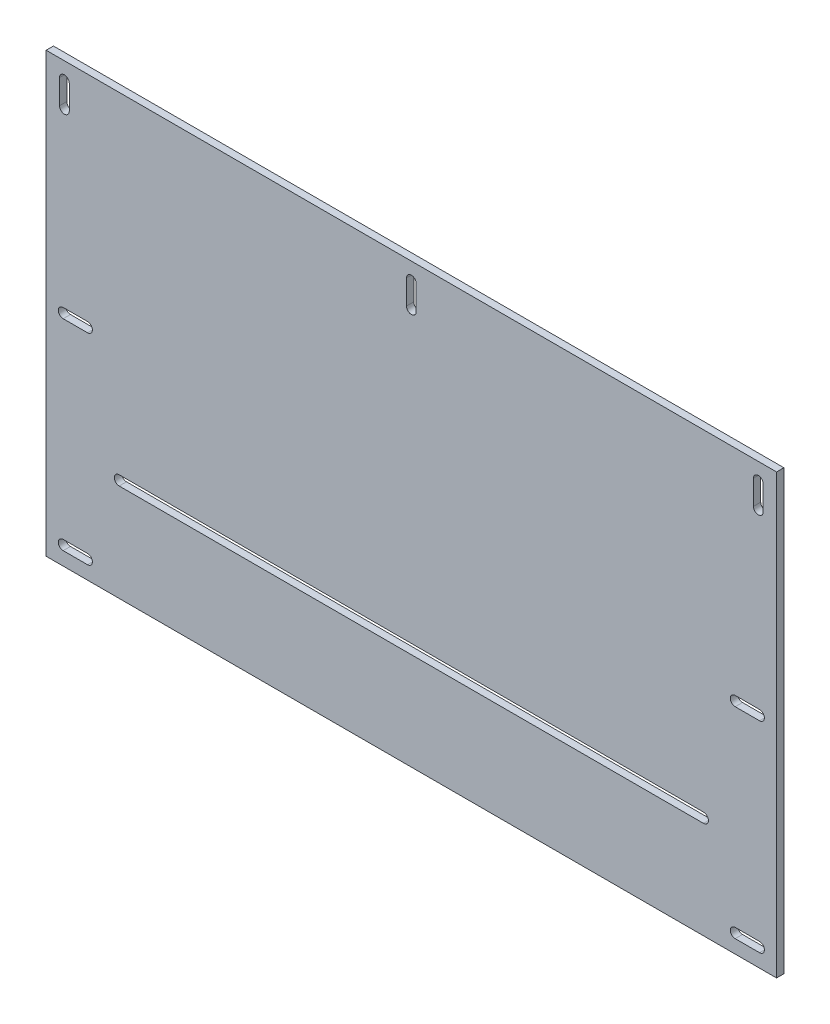
SolidWorks part; units mm, degrees
ref_plane "Front Plane" through (0, 0, 0) normal (0, 0, 1) x (1, 0, 0)
ref_plane "Top Plane" through (0, 0, 0) normal (0, 1, 0) x (1, 0, 0)
ref_plane "Right Plane" through (0, 0, 0) normal (1, 0, 0) x (0, 0, -1)
sketch "Sketch3" plane through (0, 0, 0) normal (0, 0, 1) x (1, 0, 0)
  line L1 (-150, 90) -> (150, 90)
  line L2 (-150, 90) -> (-150, -90)
  line L3 (-150, -90) -> (150, -90)
  line L4 (150, 90) -> (150, -90)
  line L5 (-150, 90) -> (150, -90) construction
  line L6 (-150, -90) -> (150, 90) construction
  point P0 (0, 0)
  dimension "D1" = 300
  dimension "D2" = 180
extrude "Boss-Extrude2" add sketch "Sketch3" along normal blind 3
sketch "Sketch4" plane through (0, 0, 3) normal (0, 0, 1) x (1, 0, 0)
  line L0 (-142.5, 83) -> (-142.5, 73) construction
  line L1 (-140.5, 83) -> (-140.5, 73)
  line L2 (-144.5, 83) -> (-144.5, 73)
  line L3 (-150, 90) -> (-150, -90) construction
  line L4 (150, 90) -> (-150, 90) construction
  line L5 (0, 83) -> (0, 73) construction
  line L6 (2, 83) -> (2, 73)
  line L7 (-2, 83) -> (-2, 73)
  line L8 (142.5, 83) -> (142.5, 73) construction
  line L9 (144.5, 83) -> (144.5, 73)
  line L10 (140.5, 83) -> (140.5, 73)
  line L11 (150, -90) -> (150, 90) construction
  arc A0 (-140.5, 83) -> (-144.5, 83) centre (-142.5, 83) ccw
  arc A1 (-144.5, 73) -> (-140.5, 73) centre (-142.5, 73) ccw
  arc A2 (2, 83) -> (-2, 83) centre (0, 83) ccw
  arc A3 (-2, 73) -> (2, 73) centre (0, 73) ccw
  arc A4 (144.5, 83) -> (140.5, 83) centre (142.5, 83) ccw
  arc A5 (140.5, 73) -> (144.5, 73) centre (142.5, 73) ccw
  point P2 (-142.5, 78)
  point P13 (0, 78)
  point P18 (142.5, 78)
  dimension "D1" = 2
  dimension "D5" = 2
  dimension "D9" = 2
  dimension "D2" = 7.5
  dimension "D3" = 7
  dimension "D4" = 10
  dimension "D6" = 10
  dimension "D7" = 7
  dimension "D8" = 150
  dimension "D10" = 10
  dimension "D11" = 7
  dimension "D12" = 7.5
extrude "Cut-Extrude1" cut sketch "Sketch4" against normal blind 3
sketch "Sketch5" plane through (0, 0, 3) normal (0, 0, 1) x (1, 0, 0)
  line L0 (-143, 0) -> (-133, 0) construction
  line L3 (-143, 2) -> (-133, 2)
  line L7 (-143, -2) -> (-133, -2)
  line L8 (-150, 90) -> (-150, -90) construction
  line L9 (150, 90) -> (-150, 90) construction
  line L10 (133, 0) -> (143, 0) construction
  line L11 (133, 2) -> (143, 2)
  line L12 (133, -2) -> (143, -2)
  line L13 (150, -90) -> (150, 90) construction
  arc A4 (-143, 2) -> (-143, -2) centre (-143, 0) ccw
  arc A5 (-133, -2) -> (-133, 2) centre (-133, 0) ccw
  arc A6 (133, 2) -> (133, -2) centre (133, 0) ccw
  arc A7 (143, -2) -> (143, 2) centre (143, 0) ccw
  point P2 (-138, 0)
  point P13 (138, 0)
  dimension "D1" = 2
  dimension "D2" = 10
  dimension "D7" = 2
  dimension "D3" = 7
  dimension "D4" = 90
  dimension "D5" = 10
  dimension "D6" = 7
  dimension "D8" = 90
extrude "Cut-Extrude2" cut sketch "Sketch5" against normal blind 3
sketch "Sketch6" plane through (0, 0, 3) normal (0, 0, 1) x (1, 0, 0)
  line L3 (143, -82.5) -> (133, -82.5) construction
  line L4 (143, -84.5) -> (133, -84.5)
  line L5 (143, -80.5) -> (133, -80.5)
  line L6 (150, -90) -> (150, 90) construction
  line L7 (-150, -90) -> (150, -90) construction
  arc A2 (143, -84.5) -> (143, -80.5) centre (143, -82.5) ccw
  arc A3 (133, -80.5) -> (133, -84.5) centre (133, -82.5) ccw
  point P7 (138, -82.5)
  dimension "D2" = 2
  dimension "D3" = 10
  dimension "D4" = 7
  dimension "D5" = 7.5
extrude "Cut-Extrude3" cut sketch "Sketch6" against normal blind 10
sketch "Sketch7" plane through (0, 0, 3) normal (0, 0, 1) x (1, 0, 0)
  line L0 (-143, -82.5) -> (-133, -82.5) construction
  line L1 (-143, -80.5) -> (-133, -80.5)
  line L2 (-143, -84.5) -> (-133, -84.5)
  line L3 (-150, -90) -> (150, -90) construction
  line L4 (-150, 90) -> (-150, -90) construction
  arc A0 (-143, -80.5) -> (-143, -84.5) centre (-143, -82.5) ccw
  arc A1 (-133, -84.5) -> (-133, -80.5) centre (-133, -82.5) ccw
  point P2 (-138, -82.5)
  dimension "D4" = 2
  dimension "D1" = 7.5
  dimension "D2" = 7
  dimension "D3" = 10
extrude "Cut-Extrude4" cut sketch "Sketch7" against normal blind 10
sketch "Sketch8" plane through (0, 0, 3) normal (0, 0, 1) x (1, 0, 0)
  line L0 (-120, -48) -> (120, -48) construction
  line L1 (-120, -46) -> (120, -46)
  line L2 (-120, -50) -> (120, -50)
  line L3 (150, -90) -> (150, 90) construction
  line L4 (-150, 90) -> (-150, -90) construction
  line L5 (150, 90) -> (-150, 90) construction
  arc A0 (-120, -46) -> (-120, -50) centre (-120, -48) ccw
  arc A1 (120, -50) -> (120, -46) centre (120, -48) ccw
  point P2 (0, -48)
  dimension "D1" = 2
  dimension "D2" = 30
  dimension "D3" = 30
  dimension "D4" = 138
extrude "Cut-Extrude5" cut sketch "Sketch8" against normal blind 10
